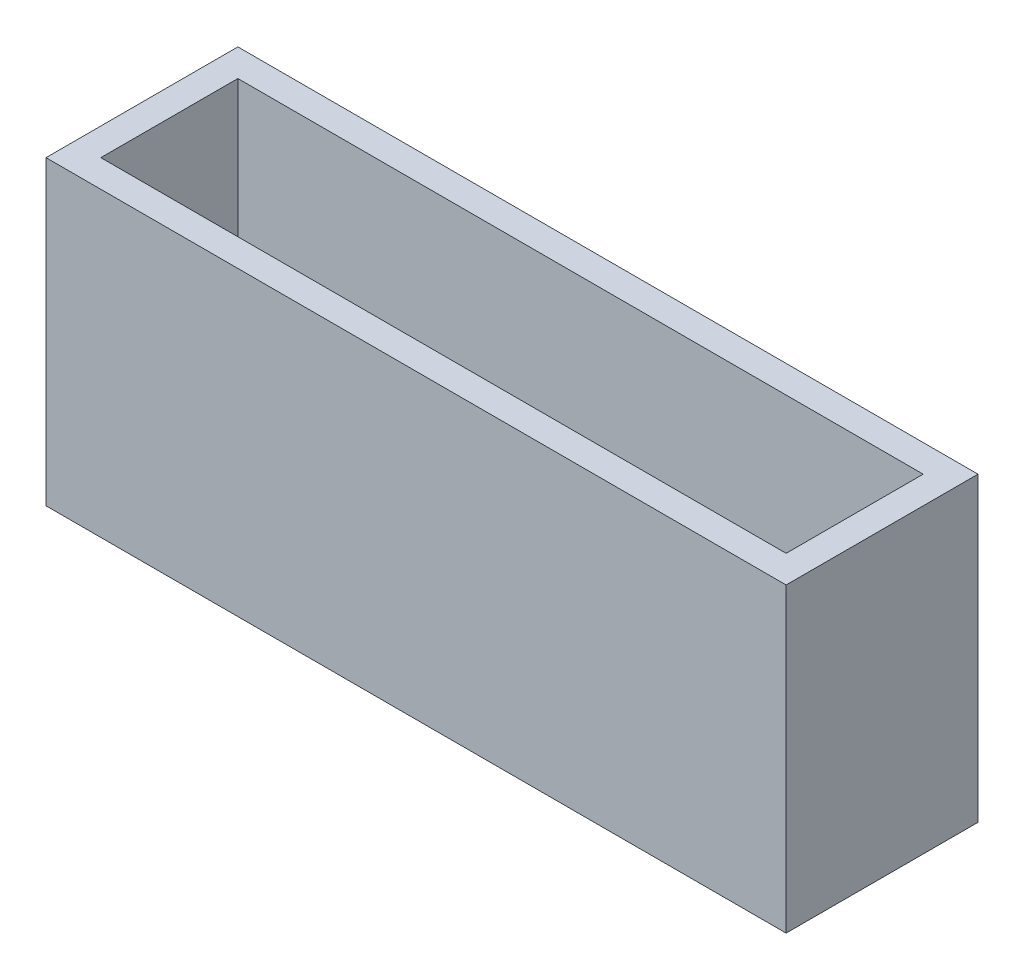
SolidWorks part; units mm, degrees
ref_plane "Front Plane" through (0, 0, 0) normal (0, 0, 1) x (1, 0, 0)
ref_plane "Top Plane" through (0, 0, 0) normal (0, 1, 0) x (1, 0, 0)
ref_plane "Right Plane" through (0, 0, 0) normal (1, 0, 0) x (0, 0, -1)
sketch "Sketch3" plane through (0, 0, 0) normal (0, 1, 0) x (1, 0, 0)
  line L1 (-27, -7) -> (27, -7)
  line L2 (-27, -7) -> (-27, 7)
  line L3 (-27, 7) -> (27, 7)
  line L4 (27, -7) -> (27, 7)
  line L5 (-27, -7) -> (27, 7) construction
  line L6 (-27, 7) -> (27, -7) construction
  line L7 (-25, -5) -> (25, -5)
  line L8 (-25, -5) -> (-25, 5)
  line L9 (-25, 5) -> (25, 5)
  line L10 (25, -5) -> (25, 5)
  line L11 (-25, -5) -> (25, 5) construction
  line L12 (-25, 5) -> (25, -5) construction
  point P0 (0, 0)
  point P6 (0, 0)
  dimension "D1" = 54
  dimension "D2" = 14
  dimension "D3" = 50
  dimension "D4" = 10
extrude "Boss-Extrude1" add sketch "Sketch3" along normal blind 22
sketch "Sketch4" plane through (0, 0, 0) normal (0, 1, 0) x (1, 0, 0)
  line L0 (25, 5) -> (-25, 5) construction
  line L1 (-18, -5) -> (18, -5)
  line L2 (-18, -5) -> (-18, 5)
  line L3 (-18, 5) -> (18, 5)
  line L4 (18, -5) -> (18, 5)
  line L5 (-18, -5) -> (18, 5) construction
  line L6 (-18, 5) -> (18, -5) construction
  line L7 (-25, -5) -> (25, -5) construction
  line L8 (-25, 5) -> (-18, 5)
  line L9 (-25, 5) -> (-25, -5)
  line L10 (-25, -5) -> (-18, -5)
  line L11 (-18, 5) -> (-18, -5)
  line L12 (18, 5) -> (25, 5)
  line L13 (18, 5) -> (18, -5)
  line L14 (18, -5) -> (25, -5)
  line L15 (25, 5) -> (25, -5)
  line L16 (25, -5) -> (25, 5) construction
  line L17 (-25, 0) -> (25, 0) construction
  line L18 (-25, 5) -> (-18, -5) construction
  line L19 (-18, 5) -> (-25, -5) construction
  line L20 (18, 5) -> (25, -5) construction
  line L21 (25, 5) -> (18, -5) construction
  circle A0 centre (-21.5, 0) radius 1
  circle A1 centre (21.5, 0) radius 1
  point P0 (0, 0)
  dimension "D2" = 2
  dimension "D1" = 36
extrude "Boss-Extrude2" add sketch "Sketch4" along normal blind 2 contours L9 L10 L2 L8 A0 | L15 L12 L4 L14 A1
